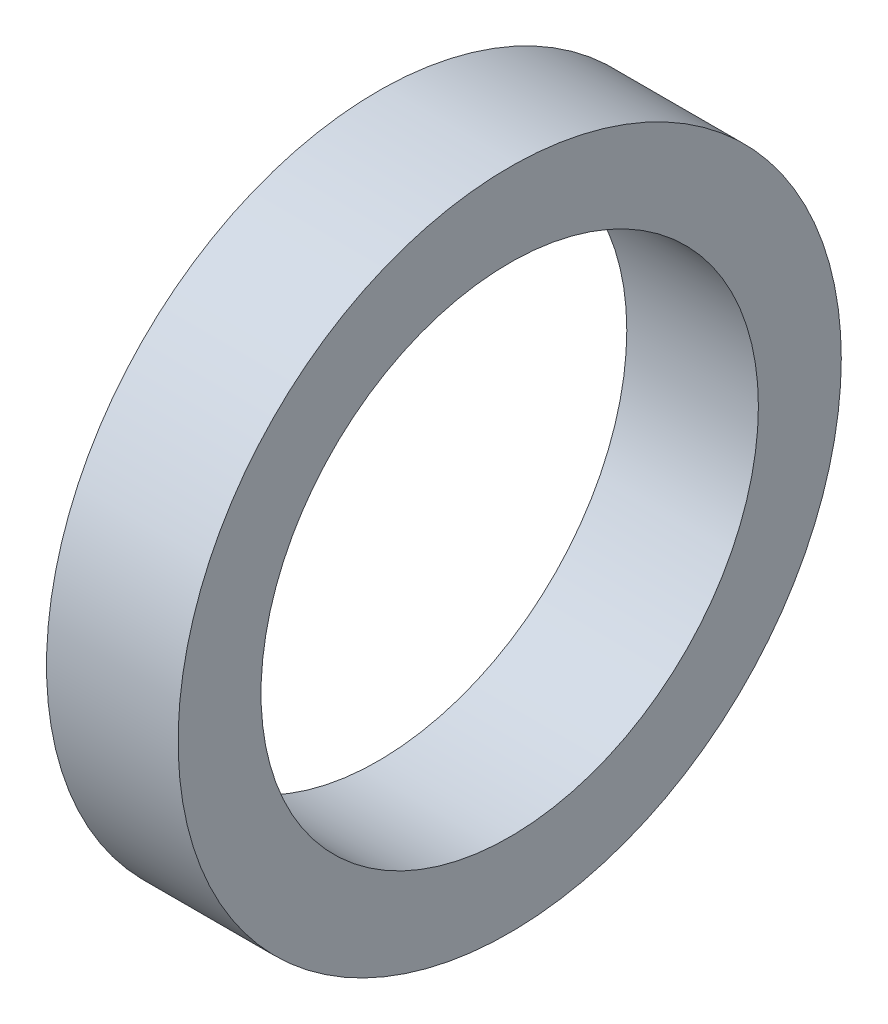
SolidWorks part; units mm, degrees
material "POM Acetal Copolymer"
ref_plane "Front Plane" through (0, 0, 0) normal (0, 0, 1) x (1, 0, 0)
ref_plane "Top Plane" through (0, 0, 0) normal (0, 1, 0) x (1, 0, 0)
ref_plane "Right Plane" through (0, 0, 0) normal (1, 0, 0) x (0, 0, -1)
sketch "Sketch1" plane through (0, 0, 0) normal (1, 0, 0) x (0, 0, -1)
  circle A0 centre (0, 0) radius 1.5
  circle A1 centre (0, 0) radius 2
  dimension "D1" = 3
  dimension "D2" = 4
extrude "Boss-Extrude1" add sketch "Sketch1" along normal blind 0.7937
